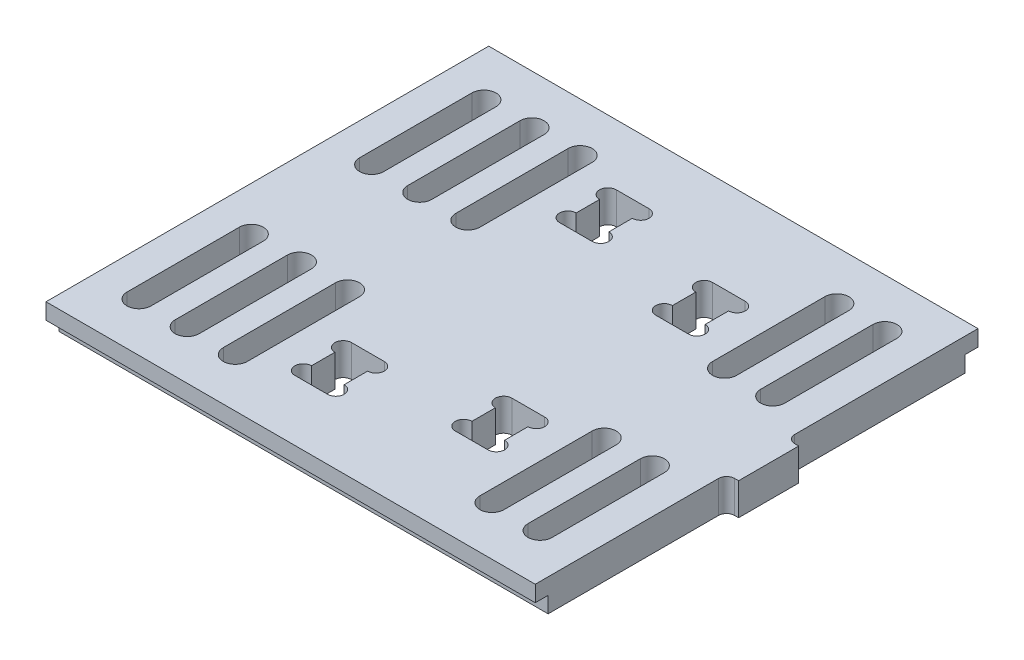
SolidWorks part; units mm, degrees
material "PE High Density"
ref_plane "Front Plane" through (0, 0, 0) normal (0, 0, 1) x (1, 0, 0)
ref_plane "Top Plane" through (0, 0, 0) normal (0, 1, 0) x (1, 0, 0)
ref_plane "Right Plane" through (0, 0, 0) normal (1, 0, 0) x (0, 0, -1)
sketch "Sketch1" plane through (0, 0, 0) normal (1, 0, 0) x (0, 0, -1)
  line L1 (-87.63, -6.35) -> (87.63, -6.35)
  line L2 (-87.63, -6.35) -> (-87.63, 6.35)
  line L3 (-87.63, 6.35) -> (87.63, 6.35)
  line L4 (87.63, -6.35) -> (87.63, 6.35)
  line L5 (-87.63, -6.35) -> (87.63, 6.35) construction
  line L6 (-87.63, 6.35) -> (87.63, -6.35) construction
  point P0 (0, 0)
  dimension "D1" = 175.26
  dimension "D2" = 12.7
extrude "Boss-Extrude1" add sketch "Sketch1" along normal mid plane 193.675
sketch "Sketch2" plane through (96.8375, 0, 0) normal (1, 0, 0) x (0, 0, -1)
  line L0 (87.63, 6.35) -> (-87.63, 6.35) construction
  line L1 (-87.63, -6.35) -> (-82.55, -6.35)
  line L2 (-87.63, -6.35) -> (-87.63, 0)
  line L3 (-87.63, 0) -> (-82.55, 0)
  line L4 (-82.55, -6.35) -> (-82.55, 0)
  line L5 (87.63, -6.35) -> (82.55, -6.35)
  line L6 (87.63, -6.35) -> (87.63, 0)
  line L7 (87.63, 0) -> (82.55, 0)
  line L8 (82.55, -6.35) -> (82.55, 0)
  dimension "D1" = 6.35
  dimension "D2" = 165.1
extrude "Cut-Extrude1" cut sketch "Sketch2" against normal through all
sketch "Sketch3" plane through (0, 6.35, 0) normal (0, 1, 0) x (1, 0, 0)
  line L0 (96.8375, 87.63) -> (96.8375, -87.63) construction
  line L1 (28.448, -28.448) -> (41.402, -28.448)
  line L2 (28.448, -35.052) -> (28.448, -44.323)
  line L3 (28.448, -50.927) -> (41.402, -50.927)
  line L4 (41.402, -35.052) -> (41.402, -44.323)
  line L17 (-22.352, -41.148) -> (-9.398, -41.148)
  line L18 (-22.352, -47.752) -> (-22.352, -57.023)
  line L19 (-22.352, -63.627) -> (-9.398, -63.627)
  line L20 (-9.398, -47.752) -> (-9.398, -57.023)
  line L21 (0, 0) -> (96.8375, 0) construction
  line L22 (-9.398, 47.752) -> (-9.398, 57.023)
  line L23 (-22.352, 63.627) -> (-9.398, 63.627)
  line L24 (-22.352, 47.752) -> (-22.352, 57.023)
  line L25 (-22.352, 41.148) -> (-9.398, 41.148)
  line L26 (41.402, 35.052) -> (41.402, 44.323)
  line L27 (28.448, 50.927) -> (41.402, 50.927)
  line L28 (28.448, 35.052) -> (28.448, 44.323)
  line L29 (28.448, 28.448) -> (41.402, 28.448)
  arc A0 (28.448, -28.448) -> (28.448, -35.052) centre (28.448, -31.75) ccw
  arc A1 (28.448, -44.323) -> (28.448, -50.927) centre (28.448, -47.625) ccw
  arc A2 (41.402, -50.927) -> (41.402, -44.323) centre (41.402, -47.625) ccw
  arc A3 (41.402, -35.052) -> (41.402, -28.448) centre (41.402, -31.75) ccw
  arc A16 (-22.352, -41.148) -> (-22.352, -47.752) centre (-22.352, -44.45) ccw
  arc A17 (-22.352, -57.023) -> (-22.352, -63.627) centre (-22.352, -60.325) ccw
  arc A18 (-9.398, -63.627) -> (-9.398, -57.023) centre (-9.398, -60.325) ccw
  arc A19 (-9.398, -47.752) -> (-9.398, -41.148) centre (-9.398, -44.45) ccw
  arc A20 (-9.398, 47.752) -> (-9.398, 41.148) centre (-9.398, 44.45) cw
  arc A21 (-9.398, 63.627) -> (-9.398, 57.023) centre (-9.398, 60.325) cw
  arc A22 (-22.352, 57.023) -> (-22.352, 63.627) centre (-22.352, 60.325) cw
  arc A23 (-22.352, 41.148) -> (-22.352, 47.752) centre (-22.352, 44.45) cw
  arc A24 (41.402, 35.052) -> (41.402, 28.448) centre (41.402, 31.75) cw
  arc A25 (41.402, 50.927) -> (41.402, 44.323) centre (41.402, 47.625) cw
  arc A26 (28.448, 44.323) -> (28.448, 50.927) centre (28.448, 47.625) cw
  arc A27 (28.448, 28.448) -> (28.448, 35.052) centre (28.448, 31.75) cw
  point P11 (34.925, -28.448)
  point P18 (41.402, -39.6875)
  point P19 (96.8375, 0)
  point P32 (-9.398, -52.3875)
  dimension "D3" = 6.604
  dimension "D6" = 3.302
  dimension "D1" = 12.954
  dimension "D2" = 22.479
  dimension "D4" = 61.9125
  dimension "D5" = 39.6875
  dimension "D7" = 22.479
  dimension "D8" = 12.954
  dimension "D9" = 52.3875
  dimension "D10" = 50.8
extrude "Cut-Extrude2" cut sketch "Sketch3" against normal through all
sketch "Sketch4" plane through (0, 6.35, 0) normal (0, 1, 0) x (1, 0, 0)
  line L0 (60.325, -68.2625) -> (60.325, -23.8125) construction
  line L1 (55.5625, -68.2625) -> (55.5625, -23.8125)
  line L2 (65.0875, -68.2625) -> (65.0875, -23.8125)
  line L3 (60.325, 23.8125) -> (60.325, 68.2625) construction
  line L4 (55.5625, 23.8125) -> (55.5625, 68.2625)
  line L5 (65.0875, 23.8125) -> (65.0875, 68.2625)
  line L6 (79.375, 68.2625) -> (79.375, 23.8125) construction
  line L7 (84.1375, 68.2625) -> (84.1375, 23.8125)
  line L8 (74.6125, 68.2625) -> (74.6125, 23.8125)
  line L9 (79.375, -23.8125) -> (79.375, -68.2625) construction
  line L10 (84.1375, -23.8125) -> (84.1375, -68.2625)
  line L11 (74.6125, -23.8125) -> (74.6125, -68.2625)
  line L12 (96.8375, 87.63) -> (96.8375, -87.63) construction
  line L13 (-79.375, -68.2625) -> (-79.375, -23.8125) construction
  line L14 (-84.1375, -68.2625) -> (-84.1375, -23.8125)
  line L15 (-74.6125, -68.2625) -> (-74.6125, -23.8125)
  line L16 (-79.375, 23.8125) -> (-79.375, 68.2625) construction
  line L17 (-84.1375, 23.8125) -> (-84.1375, 68.2625)
  line L18 (-74.6125, 23.8125) -> (-74.6125, 68.2625)
  line L19 (-96.8375, 87.63) -> (-96.8375, -87.63) construction
  line L20 (-60.325, -68.2625) -> (-60.325, -23.8125) construction
  line L21 (-65.0875, -68.2625) -> (-65.0875, -23.8125)
  line L22 (-55.5625, -68.2625) -> (-55.5625, -23.8125)
  line L23 (-60.325, 23.8125) -> (-60.325, 68.2625) construction
  line L24 (-65.0875, 23.8125) -> (-65.0875, 68.2625)
  line L25 (-55.5625, 23.8125) -> (-55.5625, 68.2625)
  line L26 (-41.275, -68.2625) -> (-41.275, -23.8125) construction
  line L27 (-46.0375, -68.2625) -> (-46.0375, -23.8125)
  line L28 (-36.5125, -68.2625) -> (-36.5125, -23.8125)
  line L29 (-41.275, 23.8125) -> (-41.275, 68.2625) construction
  line L30 (-46.0375, 23.8125) -> (-46.0375, 68.2625)
  line L31 (-36.5125, 23.8125) -> (-36.5125, 68.2625)
  line L32 (-79.375, -68.2625) -> (-60.325, -68.2625) construction
  arc A0 (55.5625, -68.2625) -> (65.0875, -68.2625) centre (60.325, -68.2625) ccw
  arc A1 (65.0875, -23.8125) -> (55.5625, -23.8125) centre (60.325, -23.8125) ccw
  arc A2 (55.5625, 23.8125) -> (65.0875, 23.8125) centre (60.325, 23.8125) ccw
  arc A3 (65.0875, 68.2625) -> (55.5625, 68.2625) centre (60.325, 68.2625) ccw
  arc A4 (84.1375, 68.2625) -> (74.6125, 68.2625) centre (79.375, 68.2625) ccw
  arc A5 (74.6125, 23.8125) -> (84.1375, 23.8125) centre (79.375, 23.8125) ccw
  arc A6 (84.1375, -23.8125) -> (74.6125, -23.8125) centre (79.375, -23.8125) ccw
  arc A7 (74.6125, -68.2625) -> (84.1375, -68.2625) centre (79.375, -68.2625) ccw
  arc A8 (-84.1375, -68.2625) -> (-74.6125, -68.2625) centre (-79.375, -68.2625) ccw
  arc A9 (-74.6125, -23.8125) -> (-84.1375, -23.8125) centre (-79.375, -23.8125) ccw
  arc A10 (-84.1375, 23.8125) -> (-74.6125, 23.8125) centre (-79.375, 23.8125) ccw
  arc A11 (-74.6125, 68.2625) -> (-84.1375, 68.2625) centre (-79.375, 68.2625) ccw
  arc A12 (-65.0875, -68.2625) -> (-55.5625, -68.2625) centre (-60.325, -68.2625) ccw
  arc A13 (-55.5625, -23.8125) -> (-65.0875, -23.8125) centre (-60.325, -23.8125) ccw
  arc A14 (-65.0875, 23.8125) -> (-55.5625, 23.8125) centre (-60.325, 23.8125) ccw
  arc A15 (-55.5625, 68.2625) -> (-65.0875, 68.2625) centre (-60.325, 68.2625) ccw
  arc A16 (-46.0375, -68.2625) -> (-36.5125, -68.2625) centre (-41.275, -68.2625) ccw
  arc A17 (-36.5125, -23.8125) -> (-46.0375, -23.8125) centre (-41.275, -23.8125) ccw
  arc A18 (-46.0375, 23.8125) -> (-36.5125, 23.8125) centre (-41.275, 23.8125) ccw
  arc A19 (-36.5125, 68.2625) -> (-46.0375, 68.2625) centre (-41.275, 68.2625) ccw
  point P2 (60.325, -46.0375)
  point P7 (60.325, 46.0375)
  point P14 (79.375, 46.0375)
  point P21 (79.375, -46.0375)
  point P30 (-79.375, -46.0375)
  point P33 (96.8375, 0)
  point P38 (-79.375, 46.0375)
  point P51 (-60.325, -46.0375)
  point P56 (-60.325, 46.0375)
  point P65 (-41.275, -46.0375)
  point P70 (-41.275, 46.0375)
  dimension "D1" = 4.7625
  dimension "D2" = 44.45
  dimension "D3" = 92.075
  dimension "D4" = 46.0375
  dimension "D6" = 19.05
  dimension "D7" = 17.4625
  dimension "D5" = 17.4625
  dimension "D9" = 19.05
  dimension "D8" = 3
extrude "Cut-Extrude3" cut sketch "Sketch4" against normal through all
sketch "Sketch5" plane through (0, 6.35, 0) normal (0, 1, 0) x (1, 0, 0)
  line L0 (96.8375, 87.63) -> (96.8375, -87.63) construction
  line L1 (96.8375, 11.9063) -> (101.6, 11.9062)
  line L2 (96.8375, 11.9063) -> (96.8375, -11.9063)
  line L3 (96.8375, -11.9063) -> (101.6, -11.9063)
  line L4 (101.6, 11.9062) -> (101.6, -11.9063)
  point P6 (101.6, 0)
  dimension "D1" = 23.8125
  dimension "D2" = 4.7625
extrude "Boss-Extrude2" add sketch "Sketch5" against normal up to surface (12.7 mm away) up to face at (-79.375, -6.35, -46.0375)
fillet "Fillet1" radius 3.175 2 edges at (96.8375, 0, -11.9063) (96.8375, 0, 11.9063)
equation "\"D1@Boss-Extrude1\"=7.66629343in "
equation "\"D5@Sketch3\"=4.125/2-.5"
equation "\"D4@Sketch4\"=\"D3@Sketch4\"/2"
equation "\"D6@Sketch3\"=\"D3@Sketch3\"/2"
equation "\"D7@Sketch3\"=\"D2@Sketch3\""
equation "\"D8@Sketch3\"=\"D1@Sketch3\""
equation "\"D9@Sketch3\"=\"D5@Sketch3\"+.5"
equation "\"D7@Sketch4\"=\"D5@Sketch4\""
